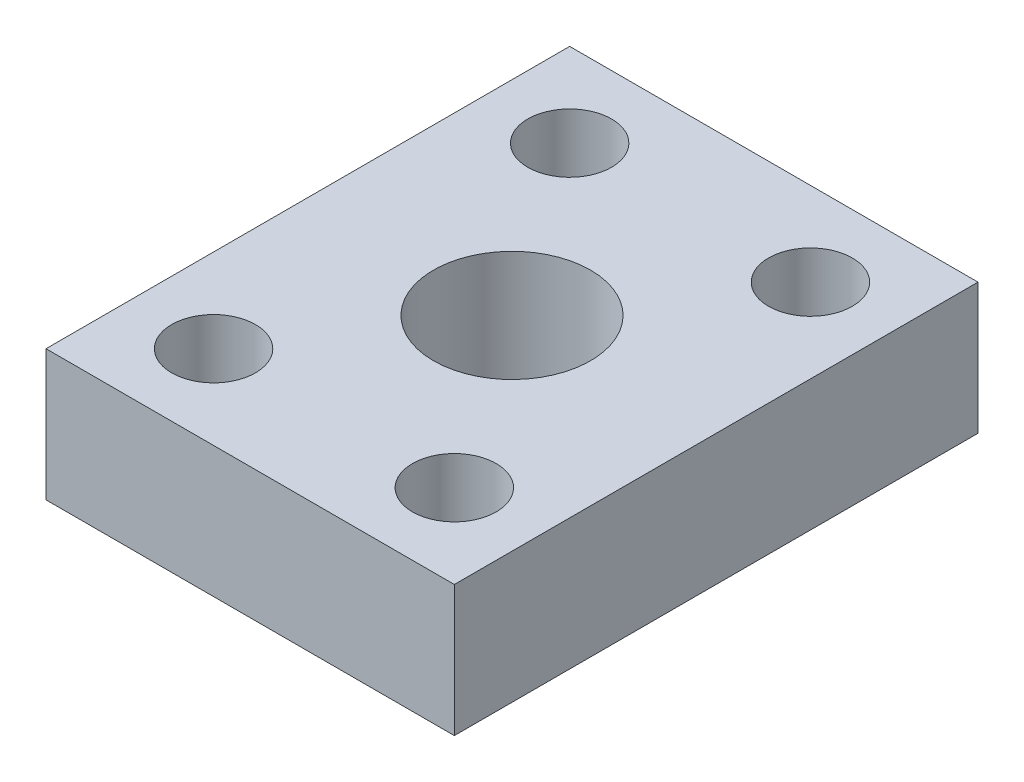
SolidWorks part; units mm, degrees
ref_plane "Front" through (0, 0, 0) normal (0, 0, 1) x (1, 0, 0)
ref_plane "Top" through (0, 0, 0) normal (0, 1, 0) x (1, 0, 0)
ref_plane "Right" through (0, 0, 0) normal (1, 0, 0) x (0, 0, -1)
sketch "Sketch1" plane through (0, 0, 0) normal (0, 1, 0) x (1, 0, 0)
  line L0 (0, 0) -> (7.62, 0) construction
  line L1 (7.62, 6.35) -> (17.5231, 6.35)
  line L2 (7.62, 6.35) -> (7.62, -6.35)
  line L3 (7.62, -6.35) -> (17.5231, -6.35)
  line L4 (17.5231, 6.35) -> (17.5231, -6.35)
  line L5 (17.5231, -38.1) -> (17.5231, 38.1) construction
  circle A0 centre (12.5715, 0) radius 1.905
  circle A1 centre (15.4911, 4.318) radius 1.016
  circle A2 centre (9.652, 4.318) radius 1.016
  circle A3 centre (9.652, -4.318) radius 1.016
  circle A4 centre (15.4911, -4.318) radius 1.016
  circle A5 centre (15.4911, -4.318) radius 1.016 construction
  circle A6 centre (12.5715, 0) radius 1.905 construction
  dimension "D1" = 7.62
  dimension "D2" = 12.7
extrude "Boss-Extrude1" add sketch "Sketch1" along normal blind 3.175
